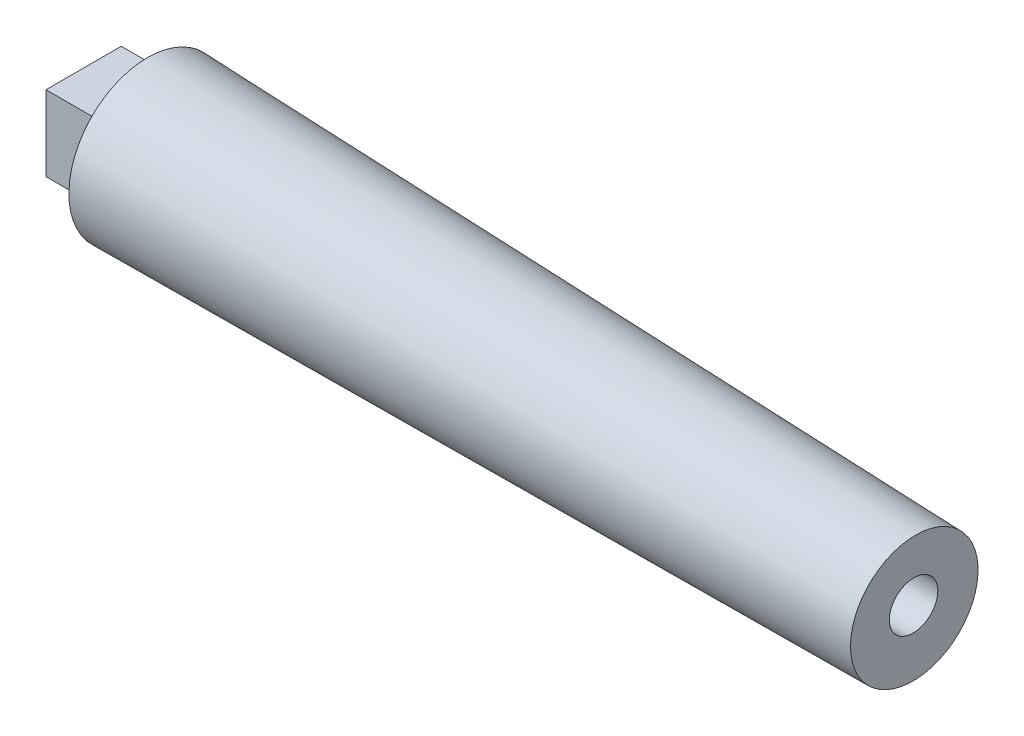
SolidWorks part; units mm, degrees
ref_plane "Front Plane" through (0, 0, 0) normal (0, 0, 1) x (1, 0, 0)
ref_plane "Top Plane" through (0, 0, 0) normal (0, 1, 0) x (1, 0, 0)
ref_plane "Right Plane" through (0, 0, 0) normal (1, 0, 0) x (0, 0, -1)
sketch "Sketch3" plane through (0, 0, 0) normal (0, 0, 1) x (1, 0, 0)
  line L0 (0, 0) -> (165.1, 0)
  line L1 (165.1, 0) -> (165.1, 12.7)
  line L2 (0, 0) -> (0, 15.875)
  line L6 (165.1, 12.7) -> (0, 15.875)
  dimension "D1" = 165.1
  dimension "D2" = 12.7
  dimension "D3" = 15.875
revolve "Revolve5" add sketch "Sketch3" angle 360 about L6
ref_plane "Plane1" through (165.1, 0, 0) normal (1, 0, 0) x (0, 0, -1)
sketch "Sketch4" plane through (165.1, 0, 0) normal (1, 0, 0) x (0, 0, -1)
  circle A0 centre (0, 13.0894) radius 4.826
  dimension "D1" = 9.652
extrude "Cut-Extrude1" cut sketch "Sketch4" against normal mid plane 25.4
sketch "Sketch5" plane through (0, 0, 0) normal (1, 0, 0) x (0, 0, -1)
  point P0 (0, 13.0894)
sketch "Sketch6" plane through (0, 0, 0) normal (1, 0, 0) x (0, 0, -1)
  circle A0 centre (0, 15.875) radius 15.875
  dimension "D1" = 31.75
extrude "Cut-Extrude2" cut sketch "Sketch6" along normal blind 12.7
sketch "Sketch7" plane through (12.7, 0, 0) normal (-1, 0, 0) x (0, 0, 1)
  ellipse E1 centre (0, 15.6366) end of major axis (0, 31.2731) minor radius 15.6337 construction
  point P0 (0, 15.6366)
  dimension "D1" = 0
sketch "Sketch8" plane through (12.7, 0, 0) normal (-1, 0, 0) x (0, 0, 1)
  line L6 (7.493, 8.1436) -> (-7.493, 8.1436)
  line L7 (7.493, 8.1436) -> (7.493, 23.1296)
  line L8 (7.493, 23.1296) -> (-7.493, 23.1296)
  line L9 (-7.493, 8.1436) -> (-7.493, 23.1296)
  point P0 (3.253, 12.8613)
extrude "Boss-Extrude1" add sketch "Sketch8" along normal blind 12.7
